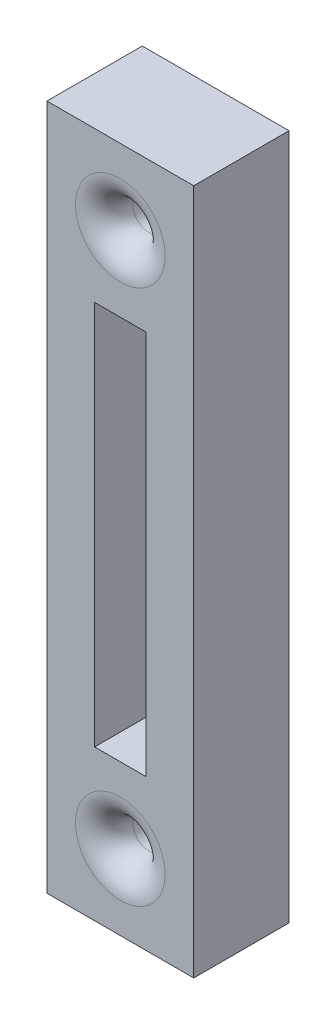
SolidWorks part; units mm, degrees
ref_plane "Front Plane" through (0, 0, 0) normal (0, 0, 1) x (1, 0, 0)
ref_plane "Top Plane" through (0, 0, 0) normal (0, 1, 0) x (1, 0, 0)
ref_plane "Right Plane" through (0, 0, 0) normal (1, 0, 0) x (0, 0, -1)
sketch "Sketch1" plane through (0, 0, 0) normal (0, 0, 1) x (1, 0, 0)
  line L1 (0, 0) -> (5.4, 0)
  line L2 (0, 0) -> (0, 40.4)
  line L3 (0, 40.4) -> (5.4, 40.4)
  line L4 (5.4, 0) -> (5.4, 40.4)
  dimension "D1" = 40.4
  dimension "D2" = 5.4
extrude "Extrude-Thin1" add sketch "Sketch1" along normal blind 10 thin
ref_plane "Plane2" through (0, 20.2, 0) normal (0, 1, 0) x (1, 0, 0)
sketch "Sketch2" plane through (0, 45.4, 0) normal (0, 1, 0) x (1, 0, 0)
  line L1 (-5, -10) -> (10.4, -10)
  line L2 (-5, -10) -> (-5, 0)
  line L3 (-5, 0) -> (10.4, 0)
  line L4 (10.4, -10) -> (10.4, 0)
extrude "Boss-Extrude1" add sketch "Sketch2" along normal blind 10.8
mirror "Mirror1" about plane through (0, 20.2, 0) normal (0, 1, 0) of "Boss-Extrude1"
sketch "Sketch3" plane through (0, 0, 0) normal (0, 0, -1) x (-1, 0, 0)
  line L0 (-2.7, 56.2) -> (-2.7, -15.8) construction
  line L1 (-10.4, 56.2) -> (5, 56.2) construction
  line L2 (-10.4, -15.8) -> (5, -15.8) construction
  line L3 (-5.4, 40.4) -> (-10.4, 40.4) construction
  line L4 (-10.4, -15.8) -> (-10.4, 56.2) construction
  line L5 (-7.9, 40.4) -> (-7.9, 56.2) construction
  line L6 (-7.9, 48.3) -> (5, 48.3) construction
  line L7 (5, 56.2) -> (5, -15.8) construction
  circle A0 centre (-2.7, 48.3) radius 1.7
  dimension "D1" = 3.4
extrude "Cut-Extrude1" cut sketch "Sketch3" against normal through all
mirror "Mirror2" about plane through (0, 20.2, 0) normal (0, 1, 0) of "Cut-Extrude1"
fillet "Fillet1" radius 3 4 edges at (1, -7.9, 0) (1, 48.3, 0) (1, -7.9, 10) (1, 48.3, 10)
